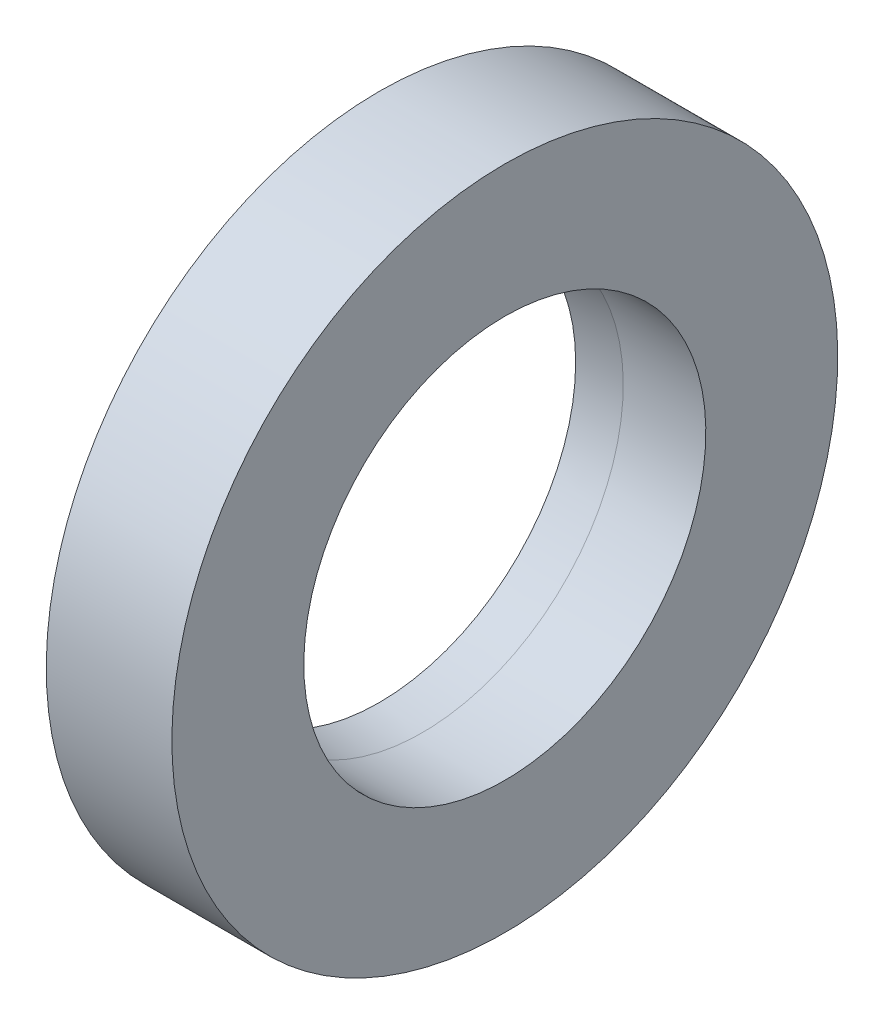
SolidWorks part; units mm, degrees
ref_plane "Alzado" through (0, 0, 0) normal (0, 0, 1) x (1, 0, 0)
ref_plane "Planta" through (0, 0, 0) normal (0, 1, 0) x (1, 0, 0)
ref_plane "Vista lateral" through (0, 0, 0) normal (1, 0, 0) x (0, 0, -1)
sketch "Croquis1" plane through (0, 0, 0) normal (0, 0, 1) x (1, 0, 0)
  line L0 (54.7364, 0) -> (0, 0) construction
  line L1 (17.7364, 26.5) -> (27.7364, 26.5)
  line L2 (27.7364, 26.5) -> (27.7364, 16)
  line L3 (27.7364, 16) -> (21.164, 16)
  line L4 (21.164, 16) -> (17.7364, 15.6394)
  line L5 (17.7364, 15.6394) -> (17.7364, 17.3108)
  line L6 (17.7364, 17.3108) -> (21.9814, 19.9863)
  line L7 (21.9862, 22.5213) -> (19.4502, 24.133)
  line L8 (19.4502, 24.133) -> (19.4502, 24.7704)
  line L9 (19.4502, 24.7704) -> (17.7364, 24.7704)
  line L10 (17.7364, 24.7704) -> (17.7364, 26.5)
  arc A0 (21.9862, 22.5213) -> (21.9814, 19.9863) centre (21.1816, 21.2553) cw
  dimension "D1" = 1.5
revolve "Revolución1" add sketch "Croquis1" angle 360 about L0
